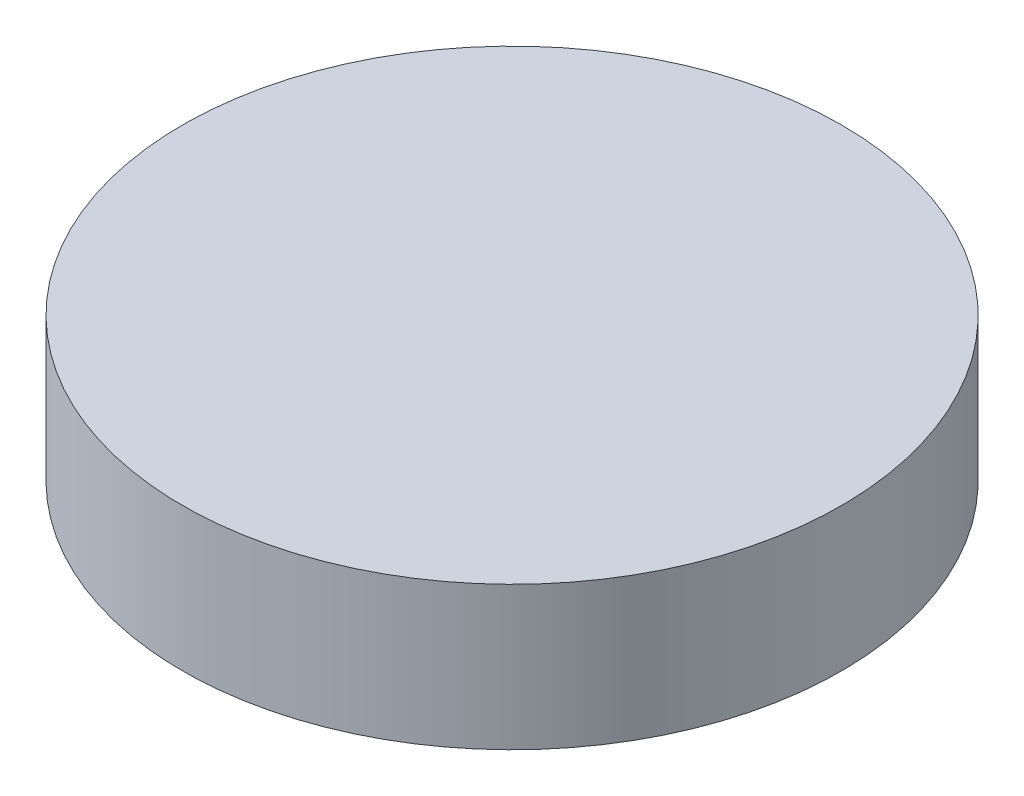
SolidWorks part; units mm, degrees
ref_plane "前视基准面" through (0, 0, 0) normal (0, 0, 1) x (1, 0, 0)
ref_plane "上视基准面" through (0, 0, 0) normal (0, 1, 0) x (1, 0, 0)
ref_plane "右视基准面" through (0, 0, 0) normal (1, 0, 0) x (0, 0, -1)
other "Configuration Table"
sketch "草图1" plane through (0, 0, 0) normal (0, 0, 1) x (1, 0, 0)
  line L0 (0, 0) -> (11.5, 0)
  line L1 (11.5, 0) -> (11.5, 5)
  line L2 (11.5, 5) -> (0, 5)
  line L3 (0, 5) -> (0, 0)
  line L4 (0, 0) -> (0, 5) construction
  dimension "radius" = 11.5
  dimension "height" = 5
revolve "Revolve" add sketch "草图1" angle 360 about L4
